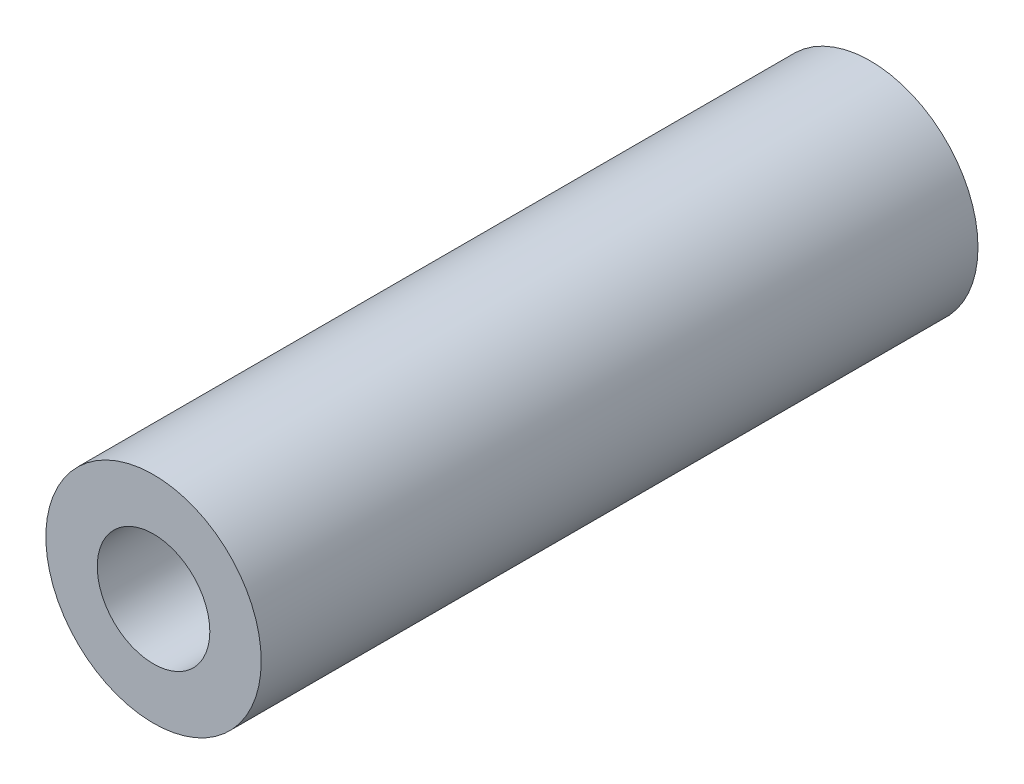
SolidWorks part; units mm, degrees
ref_plane "Front Plane" through (0, 0, 0) normal (0, 0, 1) x (1, 0, 0)
ref_plane "Top Plane" through (0, 0, 0) normal (0, 1, 0) x (1, 0, 0)
ref_plane "Right Plane" through (0, 0, 0) normal (1, 0, 0) x (0, 0, -1)
sketch "Sketch1" plane through (0, 0, 0) normal (0, 0, 1) x (1, 0, 0)
  circle A0 centre (0, 0) radius 4.7625
  circle A1 centre (0, 0) radius 2.4892
  dimension "D1" = 4.9784
  dimension "D2" = 9.525
extrude "Boss-Extrude1" add sketch "Sketch1" along normal mid plane 31.6992
